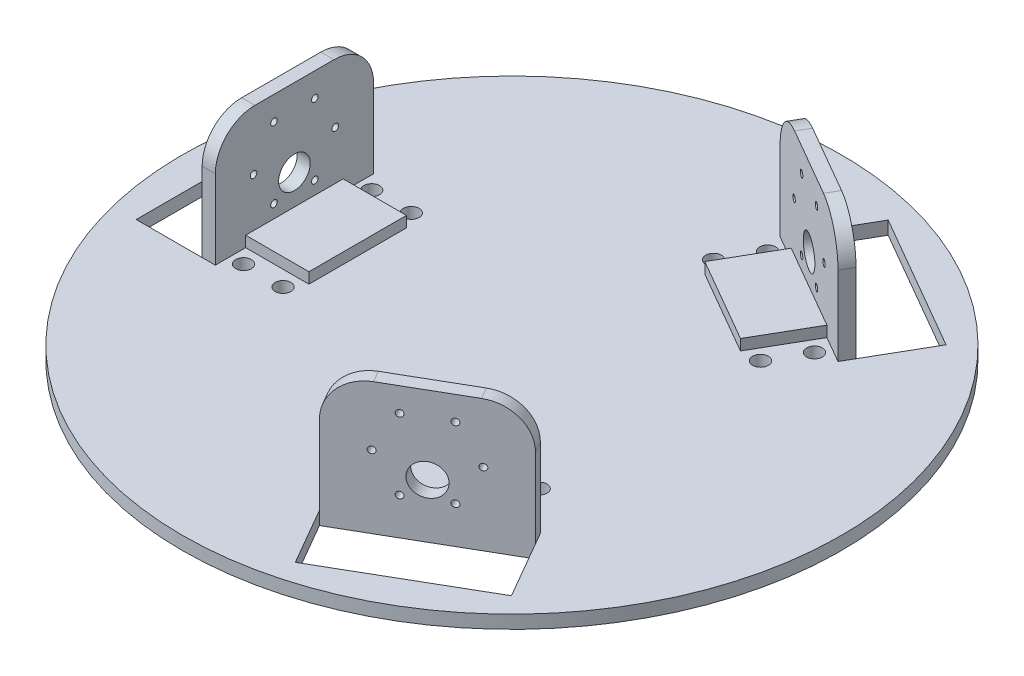
SolidWorks part; units mm, degrees
ref_plane "Plan de face" through (0, 0, 0) normal (0, 0, 1) x (1, 0, 0)
ref_plane "Plan de dessus" through (0, 0, 0) normal (0, 1, 0) x (1, 0, 0)
ref_plane "Plan de droite" through (0, 0, 0) normal (1, 0, 0) x (0, 0, -1)
sketch "Esquisse1" plane through (0, 0, 0) normal (0, 1, 0) x (1, 0, 0)
  line L0 (-148.1552, 0) -> (166.7736, 0) construction
  line L1 (-78.6345, -136.1989) -> (80.6146, 139.6286) construction
  line L2 (73.9527, -128.0898) -> (-70.9991, 122.974) construction
  line L3 (-125, 104.0914) -> (-125, -168.2709) construction
  line L4 (-112.5, 30) -> (-87.5, 30)
  line L5 (-112.5, 30) -> (-112.5, -30)
  line L6 (-112.5, -30) -> (-87.5, -30)
  line L7 (-87.5, 30) -> (-87.5, -30)
  line L8 (-112.5, 30) -> (-87.5, -30) construction
  line L9 (-112.5, -30) -> (-87.5, 30) construction
  line L10 (82.2308, 82.4279) -> (30.2692, 112.4279)
  line L11 (82.2308, 82.4279) -> (69.7308, 60.7772)
  line L12 (69.7308, 60.7772) -> (17.7692, 90.7772)
  line L13 (30.2692, 112.4279) -> (17.7692, 90.7772)
  line L14 (30.2692, -112.4279) -> (82.2308, -82.4279)
  line L15 (30.2692, -112.4279) -> (17.7692, -90.7772)
  line L16 (17.7692, -90.7772) -> (69.7308, -60.7772)
  line L17 (82.2308, -82.4279) -> (69.7308, -60.7772)
  circle A0 centre (0, 0) radius 125
  point P9 (-100, 0)
  point P27 (0, 0)
  dimension "D1" = 250
  dimension "D2" = 120
  dimension "D3" = 120
  dimension "D4" = 25
  dimension "D5" = 25
  dimension "D6" = 60
  dimension "D7" = 3
extrude "Boss.-Extru.1" add sketch "Esquisse1" along normal blind 5
sketch "Esquisse2" plane through (0, 5, 0) normal (0, 1, 0) x (1, 0, 0)
  line L1 (-87.5, -30) -> (-82.5, -30)
  line L2 (-87.5, -30) -> (-87.5, 30)
  line L3 (-87.5, 30) -> (-82.5, 30)
  line L4 (-82.5, -30) -> (-82.5, 30)
  line L5 (-129.623, 0) -> (165.3811, 0) construction
  line L6 (17.7692, 90.7772) -> (69.7308, 60.7772)
  line L7 (17.7692, 90.7772) -> (15.2692, 86.4471)
  line L8 (15.2692, 86.4471) -> (67.2308, 56.4471)
  line L9 (69.7308, 60.7772) -> (67.2308, 56.4471)
  line L10 (69.7308, -60.7772) -> (17.7692, -90.7772)
  line L11 (69.7308, -60.7772) -> (67.2308, -56.4471)
  line L12 (67.2308, -56.4471) -> (15.2692, -86.4471)
  line L13 (17.7692, -90.7772) -> (15.2692, -86.4471)
  circle A0 centre (0, 0) radius 125 construction
  circle A1 centre (0, 0) radius 125
  point P21 (0, 0)
  line M8 (-87.5, 30) -> (-87.5, -30)
  line M11 (69.7308, 60.7772) -> (17.7692, 90.7772)
  line M15 (17.7692, -90.7772) -> (69.7308, -60.7772)
  dimension "D1" = 5
  dimension "D2" = 60
  dimension "D3" = 3
extrude "Boss.-Extru.2" add sketch "Esquisse2" along normal blind 45 contours L5 L2 L1 L4 | L5 L4 L3 M8 | L9 L7 L8 M11 | L13 L11 L12 M15
fillet "Congé1" radius 15 6 edges at (68.4808, 50, 58.6122) (16.5192, 50, 88.6122) (68.4808, 50, -58.6122) (16.5192, 50, -88.6122) (-85, 50, 30) (-85, 50, -30)
sketch "Esquisse3" plane through (-87.5, 0, 0) normal (-1, 0, 0) x (0, 0, 1)
  line L0 (0, 45.2821) -> (0, 6.851) construction
  line L1 (-30, 5) -> (-30, 50) construction
  line L2 (-30, 50) -> (6.133, 50) construction
  line L3 (-15, 50) -> (15, 50) construction
  line L4 (-15, 50) -> (15, 50)
  circle A0 centre (0, 27.5) radius 19
  circle A1 centre (0, 20.5) radius 6
  circle A2 centre (7.75, 14.08) radius 1.25
  circle A3 centre (15.5, 27.5) radius 1.25
  circle A4 centre (7.75, 40.92) radius 1.25
  circle A5 centre (-7.75, 14.08) radius 1.25
  circle A6 centre (-15.5, 27.5) radius 1.25
  circle A7 centre (-7.75, 40.92) radius 1.25
  point P2 (-30, 27.5)
  dimension "D1" = 38
  dimension "D3" = 12
  dimension "D6" = 2.5
  dimension "D7" = 2.5
  dimension "D8" = 2.5
  dimension "D2" = 7
  dimension "D4" = 7.75
  dimension "D5" = 13.42
  dimension "D9" = 15.5
  dimension "D10" = 7.75
  dimension "D11" = 13.42
extrude "Enlèv. mat.-Extru.1" cut sketch "Esquisse3" against normal blind 50 contours A1 | A5 | A6 | A7 | A4 | A3 | A2
sketch "Esquisse4" plane through (-87.5, 0, 0) normal (-1, 0, 0) x (0, 0, 1)
  line L0 (-15, 50) -> (15, 50) construction
  line L1 (-15, 50) -> (15, 50)
  circle A1 centre (15.5, 27.5) radius 1.25
  circle A2 centre (15.5, 27.5) radius 1.25
  circle A3 centre (7.75, 14.08) radius 1.25
  circle A4 centre (7.75, 14.08) radius 1.25
  circle A5 centre (0, 20.5) radius 6
  circle A6 centre (0, 20.5) radius 6
  circle A7 centre (0, 27.5) radius 19
  circle A8 centre (0, 27.5) radius 19
  circle A9 centre (-7.75, 40.92) radius 1.25
  circle A10 centre (-7.75, 40.92) radius 1.25
  circle A11 centre (-15.5, 27.5) radius 1.25
  circle A12 centre (-15.5, 27.5) radius 1.25
  circle A13 centre (-7.75, 14.08) radius 1.25
  circle A14 centre (-7.75, 14.08) radius 1.25
  circle A15 centre (7.75, 40.92) radius 1.25
  circle A16 centre (7.75, 40.92) radius 1.25
  dimension "D1" = 0
  dimension "D2" = 0
  dimension "D3" = 0
  dimension "D4" = 0
  dimension "D5" = 0
  dimension "D6" = 0
  dimension "D7" = 0
  dimension "D8" = 0
pattern_circular "Répétition circulaire1" count 3 every 120 about axis through (0, 5, 0) along (0, 1, 0) of "Enlèv. mat.-Extru.1"
sketch "Esquisse5" plane through (43.75, 0, -75.7772) normal (0.5, 0, -0.866) x (-0.866, 0, -0.5)
  circle A0 centre (0, 20.5) radius 6 construction
  circle A1 centre (0, 20.5) radius 6
  circle A3 centre (0, 27.5) radius 4.0002
  dimension "D1" = 7
sketch "Esquisse6" plane through (43.75, 0, 75.7772) normal (0.5, 0, 0.866) x (0.866, 0, -0.5)
  circle A0 centre (0, 20.5) radius 6 construction
  circle A1 centre (0, 20.5) radius 6
  circle A2 centre (0, 27.5) radius 4.2191
  point P5 (0, 0)
  dimension "D1" = 7
sketch "Esquisse7" plane through (0, 5, 0) normal (0, 1, 0) x (1, 0, 0)
  line L0 (-112.5, 0) -> (37.0508, 0) construction
  line L1 (-112.5, 30) -> (-112.5, -30) construction
  line L2 (-82.5, -30) -> (-82.5, 30) construction
  line L3 (-58.5, -18.5) -> (-82.5, -18.5)
  line L4 (-58.5, -18.5) -> (-58.5, 18.5)
  line L5 (-58.5, 18.5) -> (-82.5, 18.5)
  line L6 (-82.5, -18.5) -> (-82.5, 18.5)
  line L7 (-58.5, -18.5) -> (-82.5, 18.5) construction
  line L8 (-58.5, 18.5) -> (-82.5, -18.5) construction
  point P5 (-70.5, 0)
  point P13 (0, 0)
  point P14 (0, 0)
  point P15 (-58.5, 35.3273)
  point P17 (0, 0)
  line M26 (-82.5, 30) -> (-82.5, -30)
  dimension "D1" = 37
  dimension "D2" = 24
extrude "Boss.-Extru.4" add sketch "Esquisse7" along normal blind 4.1 contours L4 L5 L3 M26
sketch "Esquisse8" plane through (0, 5, 0) normal (0, 1, 0) x (1, 0, 0)
  line L0 (0, 0) -> (-184.2345, 0) construction
  line L1 (-82.5, 15) -> (-82.5, 30) construction
  line L2 (-58.5, 18.5) -> (-82.5, 18.5) construction
  circle A0 centre (-77.5, 24.304) radius 3
  circle A1 centre (-62.5, 24.304) radius 3
  circle A2 centre (-62.5, -24.304) radius 3
  circle A3 centre (-77.5, -24.304) radius 3
  point P11 (0, 0)
  dimension "D1" = 6
  dimension "D2" = 6
  dimension "D3" = 5
  dimension "D4" = 15
  dimension "D5" = 5.804
extrude "Enlèv. mat.-Extru.2" cut sketch "Esquisse8" against normal through all
pattern_circular "Répétition circulaire2" count 3 every 120 about axis through (0, 0, 0) along (0, 1, 0) of "Boss.-Extru.4", "Enlèv. mat.-Extru.2"
